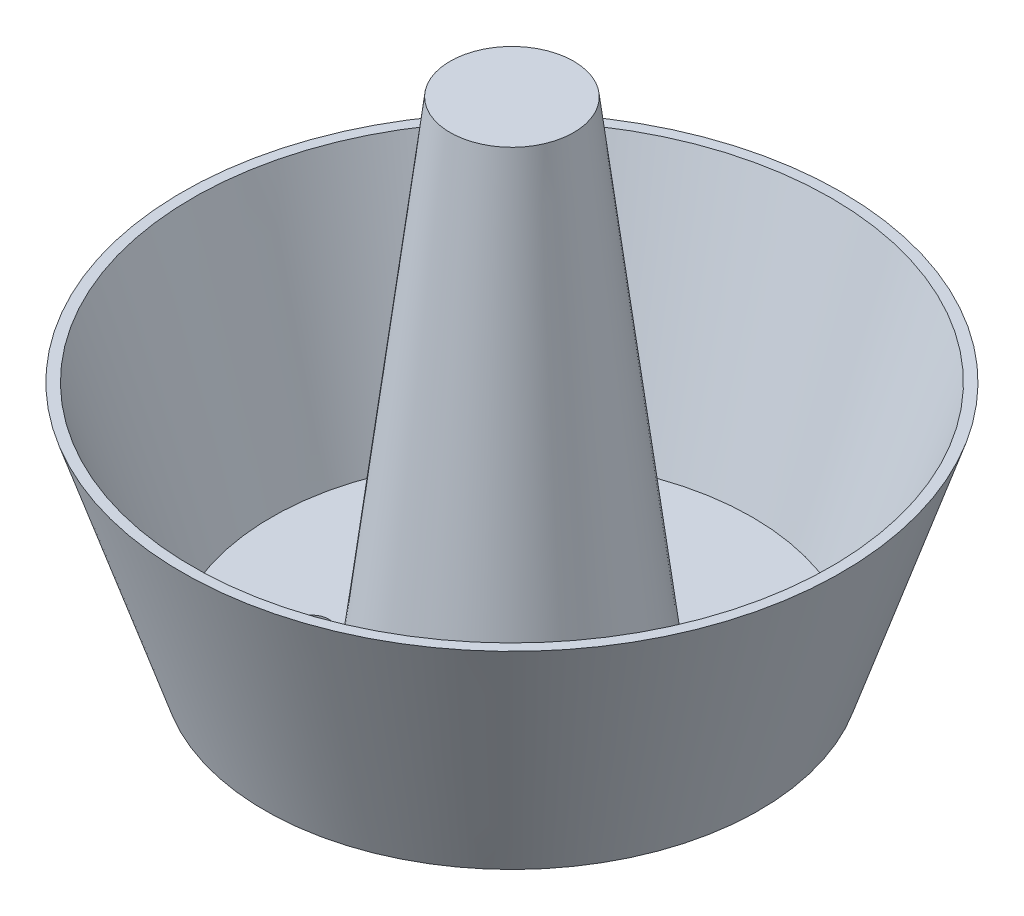
SolidWorks part; units mm, degrees
ref_plane "Front" through (0, 0, 0) normal (0, 0, 1) x (1, 0, 0)
ref_plane "Top" through (0, 0, 0) normal (0, 1, 0) x (1, 0, 0)
ref_plane "Right" through (0, 0, 0) normal (1, 0, 0) x (0, 0, -1)
sketch "Sketch1" plane through (0, 0, 0) normal (0, 0, 1) x (1, 0, 0)
  line L0 (0, 152.4) -> (19.05, 152.4)
  line L1 (0, -50) -> (0, 50) construction
  line L2 (19.05, 152.4) -> (37.3412, 3.175)
  line L3 (37.3412, 3.175) -> (74.0833, 3.175)
  line L4 (74.0833, 3.175) -> (98.425, 76.2)
  line L5 (98.425, 76.2) -> (101.6, 76.2)
  line L6 (101.6, 76.2) -> (76.2, 0)
  line L7 (50, 0) -> (-50, 0) construction
  line L8 (76.2, 0) -> (0, 0)
  line L9 (0, 0) -> (0, 152.4)
  dimension "D1" = 152.4
  dimension "D2" = 3.175
  dimension "D3" = 76.2
  dimension "D4" = 76.2
  dimension "D5" = 3.175
  dimension "D6" = 19.05
  dimension "D7" = 101.6
revolve "Revolve1" add sketch "Sketch1" angle 360 about L9
sketch "Sketch4" plane through (0, 0, 0) normal (0, -1, 0) x (1, 0, 0)
  line L0 (0, 0) -> (0, 23.4938) construction
  line L1 (0, 23.4938) -> (38.1, 23.4938) construction
  line L2 (0, 23.4938) -> (-38.1, 23.4938) construction
  dimension "D1" = 76.2
hole_wizard "3/8 Clearance Hole1" positions "Sketch6" profile "Sketch5" hole size "3/8" standard "ANSI Inch" end condition through all
sketch "Sketch6" plane through (0, 0, 0) normal (0, -1, 0) x (-1, 0, 0)
  point P0 (38.1, -23.4938)
  point P3 (-38.1, -23.4938)
sketch "Sketch5" plane through (-38.1, 0, 23.4938) normal (1, 0, 0) x (0, 0, -1)
  line L0 (0, 0) -> (0, 152.4)
  line L1 (0, 152.4) -> (5.0419, 152.4)
  line L2 (5.0419, 152.4) -> (5.0419, 0)
  line L5 (5.0419, 0) -> (0, 0)
  line L11 (0, -6.35) -> (0, 107.95) construction
  dimension "Thru Hole Dia." = 10.0838
  dimension "Thru Hole Depth" = 152.4
sketch "Sketch2" plane through (0, 0, 0) normal (0, -1, 0) x (1, 0, 0)
  circle A0 centre (0, 0) radius 12.7
  dimension "D1" = 25.4
extrude "RF Connector" add sketch "Sketch2" along normal blind 25.4
